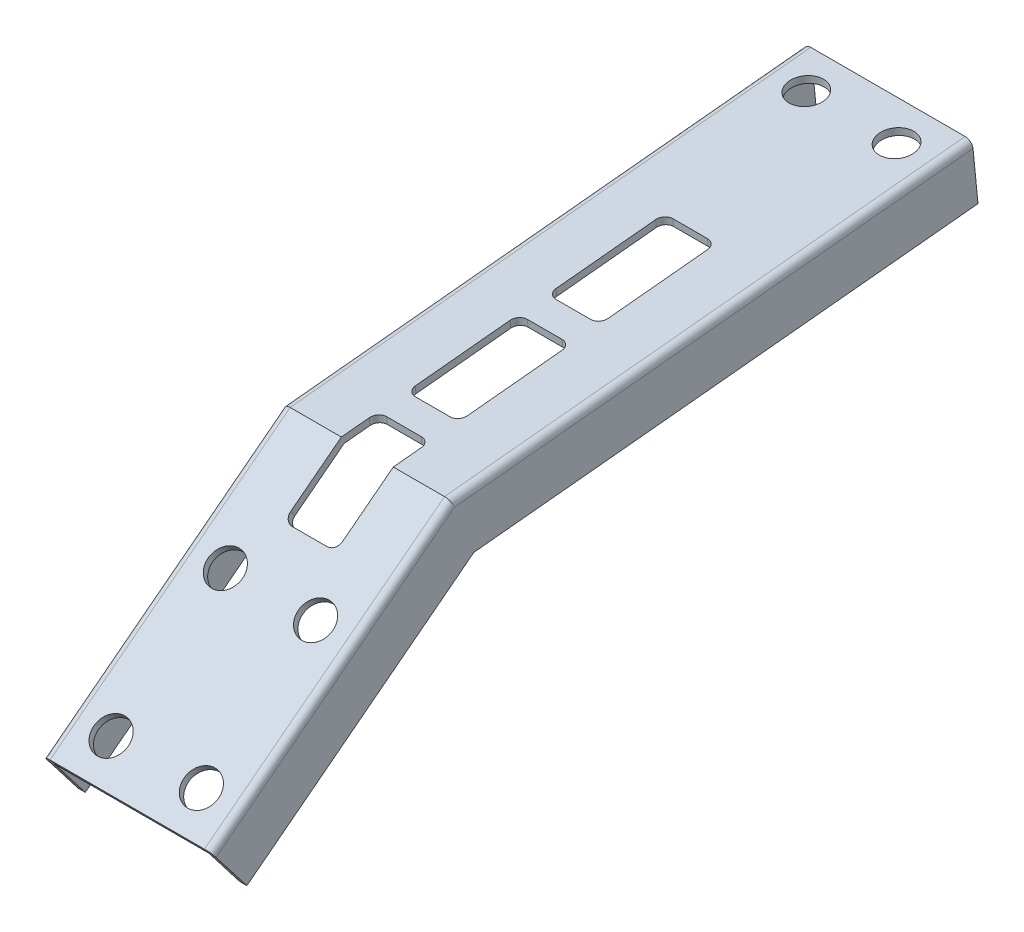
SolidWorks part; units mm, degrees
material "AISI 1020"
ref_plane "Front Plane" through (0, 0, 0) normal (0, 0, 1) x (1, 0, 0)
ref_plane "Top Plane" through (0, 0, 0) normal (0, 1, 0) x (1, 0, 0)
ref_plane "Right Plane" through (0, 0, 0) normal (1, 0, 0) x (0, 0, -1)
sketch "Sketch1" plane through (0, 0, 0) normal (1, 0, 0) x (0, 0, -1)
  line L0 (45.4439, 24.7163) -> (-44.4073, 15.8142)
  line L1 (-85.7256, -16.072) -> (-44.4073, 15.8142)
  line L2 (-86.4893, -15.0824) -> (-44.8872, 17.0228)
  line L3 (45.3206, 25.9602) -> (-44.8872, 17.0228)
  line L4 (-85.7256, -16.072) -> (-86.4893, -15.0824)
  line L5 (45.3206, 25.9602) -> (45.4439, 24.7163)
extrude "Boss-Extrude1" add sketch "Sketch1" along normal blind 26.75
sketch "Sketch2" plane through (26.75, 0, 0) normal (1, 0, 0) x (0, 0, -1)
  line L10 (46.3065, 16.009) -> (-41.0478, 7.3542)
  line L11 (-41.0478, 7.3542) -> (-80.3798, -22.9991)
  line L15 (-44.8872, 17.0228) -> (-86.4893, -15.0824)
  line L16 (45.3206, 25.9602) -> (-44.8872, 17.0228)
  line L17 (-44.8872, 17.0228) -> (-86.4893, -15.0824)
  line L24 (45.3206, 25.9602) -> (-44.8872, 17.0228)
  line L33 (-80.3798, -22.9991) -> (-86.4893, -15.0824)
  line L34 (46.3065, 16.009) -> (45.3206, 25.9602)
  dimension "D1" = 0
  dimension "D2" = 10
sketch "Sketch4" plane through (0, 21.2613, 2.1065) normal (0, 0.9951, 0.0986) x (1, 0, 0)
  line L0 (0, 47.6593) -> (26.75, 47.6593) construction
  line L1 (13.375, 47.6593) -> (13.375, -42.9902) construction
  line L2 (26.75, -42.9902) -> (0, -42.9902) construction
  point P8 (0, 0)
ref_plane "Plane1" through (13.375, 0, 0) normal (1, 0, 0) x (0, 0, -1)
extrude "Boss-Extrude2" add sketch "Sketch2" along normal blind 1.25
fillet "Fillet1" radius 1.25 2 edges at (28, 21.4915, -0.2167) (28, 0.9702, 65.6883)
mirror "Mirror1" about plane through (13.375, 0, 0) normal (1, 0, 0) of "Fillet1", "Boss-Extrude2"
sketch "Sketch5" plane through (0, 21.2613, 2.1065) normal (0, 0.9951, 0.0986) x (1, 0, 0)
  line L0 (0, 47.6593) -> (26.75, 47.6593) construction
  line L1 (13.375, 47.6593) -> (13.375, 41.3093) construction
  line L2 (13.375, 47.6593) -> (13.375, -42.9902) construction
  line L3 (21.1937, 41.3093) -> (5.5563, 41.3093) construction
  circle A0 centre (5.5563, 41.3093) radius 3
  circle A1 centre (21.1937, 41.3093) radius 3
  point P12 (13.375, 41.3093)
extrude "Cut-Extrude1" cut sketch "Sketch5" against normal blind 1.25
sketch "Sketch6" plane through (0, 32.3795, 24.988) normal (0, 0.7917, 0.6109) x (1, 0, 0)
  line L0 (0, -77.6855) -> (26.75, -77.6855) construction
  line L1 (13.375, -77.6855) -> (13.375, -71.3355) construction
  line L2 (5.5563, -71.3355) -> (21.1938, -71.3355) construction
  line L3 (5.5563, -46.3355) -> (21.1938, -46.3355) construction
  circle A0 centre (21.1938, -71.3355) radius 3
  circle A1 centre (5.5563, -71.3355) radius 3
  circle A2 centre (5.5563, -46.3355) radius 3
  circle A3 centre (21.1938, -46.3355) radius 3
  point P8 (13.375, -71.3355)
  dimension "D1" = 25
extrude "Cut-Extrude2" cut sketch "Sketch6" against normal blind 1.25
sketch "Sketch7" plane through (0, 21.2613, 2.1065) normal (0, 0.9951, 0.0986) x (1, 0, 0)
  line L0 (13.375, 47.6593) -> (13.375, -42.9902) construction
  line L1 (8.875, -42.9438) -> (17.875, -42.9438)
  line L2 (8.875, -42.9438) -> (8.875, -38.105)
  line L4 (17.875, -42.9438) -> (17.875, -38.105)
  line L5 (8.875, -42.9438) -> (17.136, 13.235) construction
  line L6 (9.614, 13.235) -> (16.2076, -31.605) construction
  line L8 (17.875, -23.605) -> (17.875, -15.105)
  line L10 (8.875, -23.605) -> (8.875, -15.105)
  line L11 (16.375, 13.235) -> (10.375, 13.235)
  line L12 (10.375, -36.605) -> (16.375, -36.605)
  line L13 (10.375, -31.605) -> (16.375, -31.605)
  line L16 (8.875, -23.605) -> (8.875, -28.605)
  line L17 (17.875, -28.605) -> (17.875, -23.605)
  line L18 (17.875, -5.605) -> (17.875, 11.735)
  line L19 (8.875, -5.605) -> (8.875, 11.735)
  line L20 (8.875, -30.105) -> (8.875, -28.605)
  line L21 (17.875, -30.105) -> (17.875, -28.605)
  line L22 (16.9429, -36.605) -> (17.875, -42.9438) construction
  line L23 (10.375, -7.105) -> (16.375, -7.105)
  line L24 (10.375, -12.105) -> (16.375, -12.105)
  line L25 (8.875, -13.605) -> (8.875, -15.105)
  line L26 (17.875, -13.605) -> (17.875, -15.105)
  arc A2 (10.375, 13.235) -> (8.875, 11.735) centre (10.375, 11.735) ccw
  arc A3 (16.375, 13.235) -> (17.875, 11.735) centre (16.375, 11.735) cw
  arc A6 (10.375, -31.605) -> (8.875, -30.105) centre (10.375, -30.105) cw
  arc A7 (17.875, -30.105) -> (16.375, -31.605) centre (16.375, -30.105) cw
  arc A8 (10.375, -36.605) -> (8.875, -38.105) centre (10.375, -38.105) ccw
  arc A9 (17.875, -38.105) -> (16.375, -36.605) centre (16.375, -38.105) ccw
  arc A10 (8.875, -5.605) -> (10.375, -7.105) centre (10.375, -5.605) ccw
  arc A11 (17.875, -5.605) -> (16.375, -7.105) centre (16.375, -5.605) cw
  arc A12 (10.375, -12.105) -> (8.875, -13.605) centre (10.375, -13.605) ccw
  arc A13 (17.875, -13.605) -> (16.375, -12.105) centre (16.375, -13.605) ccw
  point P0 (13.375, -12.3418)
  point P44 (13.375, -10.8418)
  dimension "D3" = 1.5
  dimension "D4" = 1.5
  dimension "D7" = 1.5
  dimension "D8" = 1.5
  dimension "D9" = 1.5
  dimension "D10" = 1.5
  dimension "D11" = 1.5
  dimension "D12" = 1.5
extrude "Cut-Extrude3" cut sketch "Sketch7" against normal blind 1.25
sketch "Sketch8" plane through (0, 32.3795, 24.988) normal (0, 0.7917, 0.6109) x (1, 0, 0)
  line L0 (8.875, -25.0965) -> (8.875, -36.2451)
  line L1 (10.375, -37.7451) -> (16.375, -37.7451)
  line L2 (17.875, -36.2451) -> (17.875, -25.0965)
  line L3 (17.875, -25.0965) -> (8.875, -25.0965)
  arc A0 (10.375, -37.7451) -> (8.875, -36.2451) centre (10.375, -36.2451) cw
  arc A1 (17.875, -36.2451) -> (16.375, -37.7451) centre (16.375, -36.2451) cw
  dimension "D1" = 1.5
  dimension "D2" = 1.5
extrude "Cut-Extrude4" cut sketch "Sketch8" against normal blind 1.25
